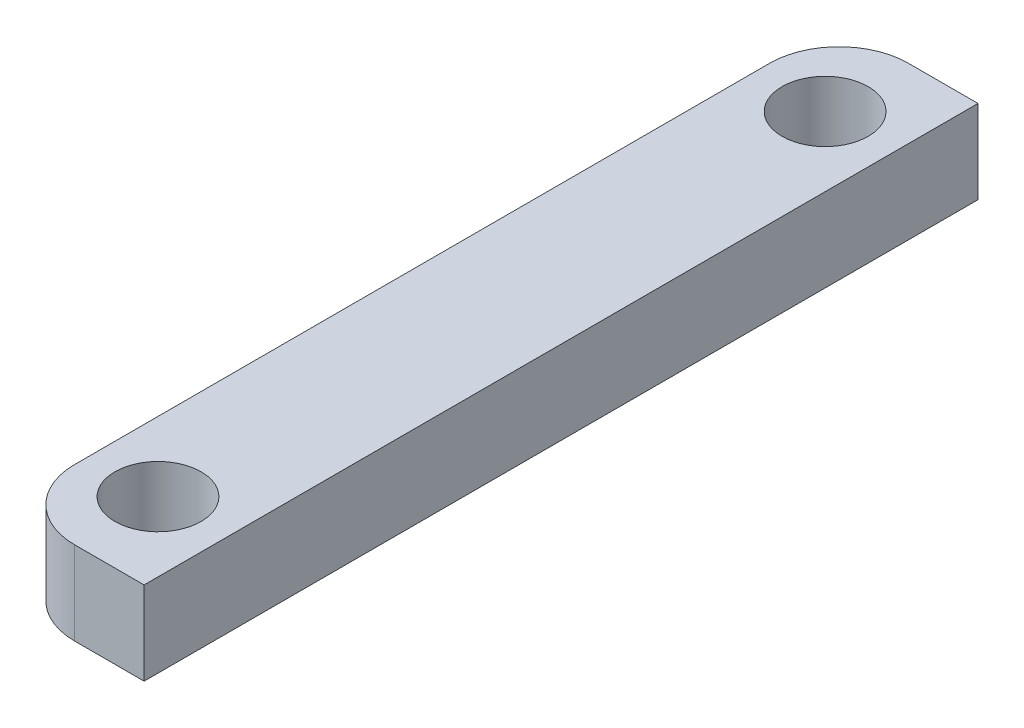
SolidWorks part; units mm, degrees
ref_plane "Front Plane" through (0, 0, 0) normal (0, 0, 1) x (1, 0, 0)
ref_plane "Top Plane" through (0, 0, 0) normal (0, 1, 0) x (1, 0, 0)
ref_plane "Right Plane" through (0, 0, 0) normal (1, 0, 0) x (0, 0, -1)
sketch "Sketch1" plane through (0, 0, 0) normal (0, 1, 0) x (1, 0, 0)
  line L1 (-2.5, -15) -> (2.5, -15)
  line L2 (-2.5, -15) -> (-2.5, 15)
  line L3 (-2.5, 15) -> (2.5, 15)
  line L4 (2.5, -15) -> (2.5, 15)
  line L5 (-2.5, -15) -> (2.5, 15) construction
  line L6 (-2.5, 15) -> (2.5, -15) construction
  circle A0 centre (0, 12) radius 1.55
  circle A1 centre (0, -12) radius 1.55
  point P0 (0, 0)
  point P10 (0, 0)
  dimension "D3" = 3.1
  dimension "D4" = 3.1
  dimension "D1" = 5
  dimension "D2" = 30
  dimension "D5" = 3
  dimension "D6" = 3
  dimension "D7" = 2.5
  dimension "D8" = 2.5
extrude "Boss-Extrude1" add sketch "Sketch1" along normal blind 3
fillet "Fillet1" radius 2.5 2 edges at (-2.5, 1.5, 15) (-2.5, 1.5, -15)
